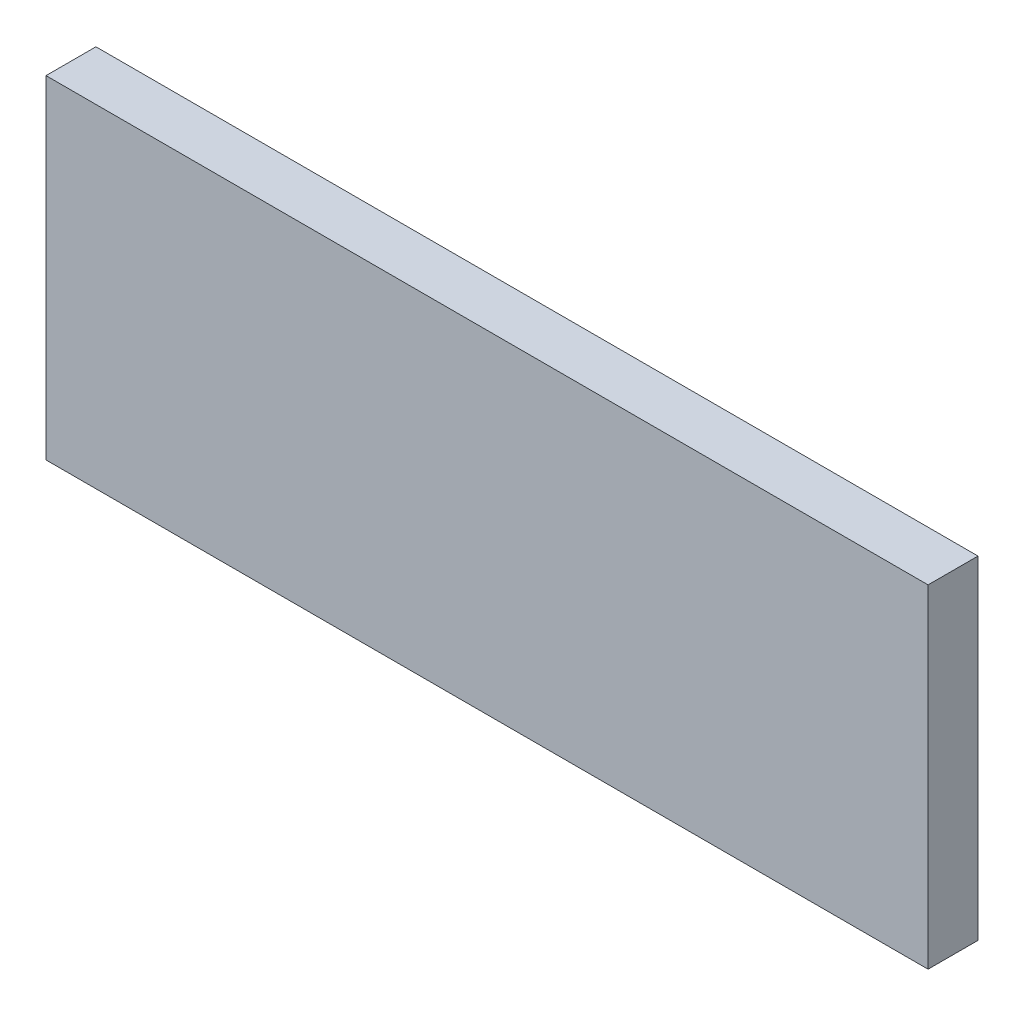
SolidWorks part; units mm, degrees
ref_plane "Front Plane" through (0, 0, 0) normal (0, 0, 1) x (1, 0, 0)
ref_plane "Top Plane" through (0, 0, 0) normal (0, 1, 0) x (1, 0, 0)
ref_plane "Right Plane" through (0, 0, 0) normal (1, 0, 0) x (0, 0, -1)
sketch "Sketch1" plane through (0, 0, 0) normal (0, 0, 1) x (1, 0, 0)
  line L1 (-132.5, -50) -> (132.5, -50)
  line L2 (-132.5, -50) -> (-132.5, 50)
  line L3 (-132.5, 50) -> (132.5, 50)
  line L4 (132.5, -50) -> (132.5, 50)
  line L5 (-132.5, -50) -> (132.5, 50) construction
  line L6 (-132.5, 50) -> (132.5, -50) construction
  point P0 (0, 0)
  dimension "D1" = 265
  dimension "D2" = 100
extrude "Boss-Extrude1" add sketch "Sketch1" along normal blind 15
